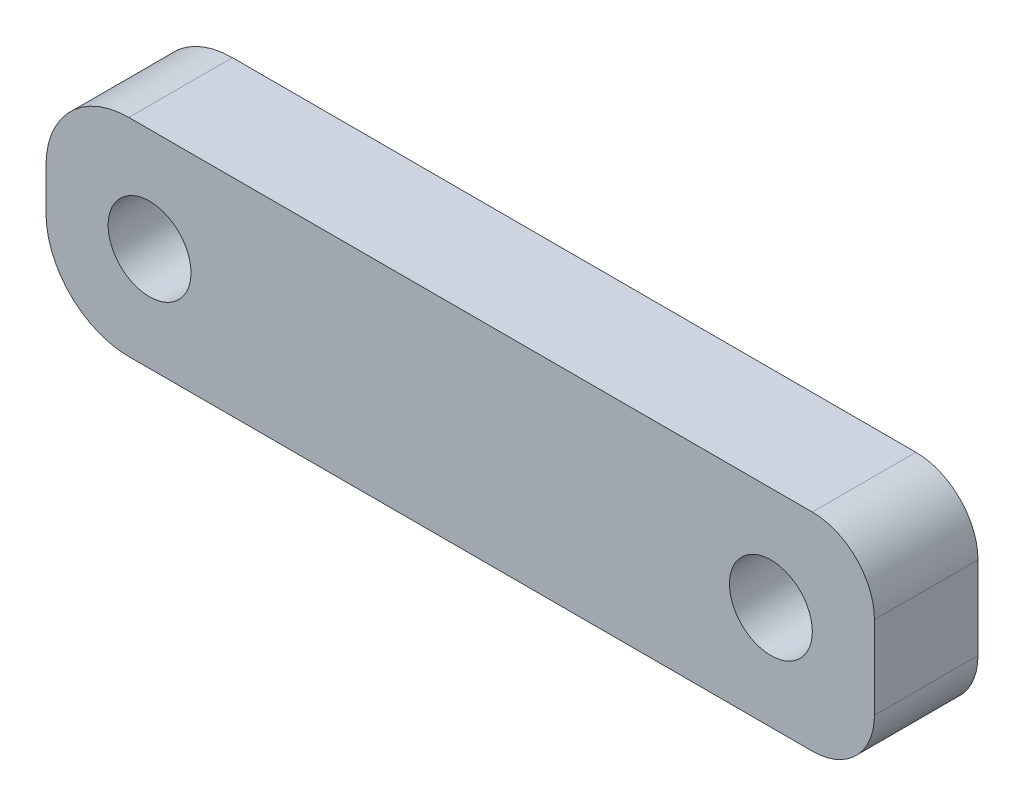
SolidWorks part; units mm, degrees
material "6061 合金"
ref_plane "前视基准面" through (0, 0, 0) normal (0, 0, 1) x (1, 0, 0)
ref_plane "上视基准面" through (0, 0, 0) normal (0, 1, 0) x (1, 0, 0)
ref_plane "右视基准面" through (0, 0, 0) normal (1, 0, 0) x (0, 0, -1)
other "Configuration Table"
sketch "草图1" plane through (0, 0, 0) normal (0, 0, 1) x (1, 0, 0)
  line L1 (4, 0) -> (37, 0)
  line L2 (0, -4) -> (0, -6)
  line L3 (4, -10) -> (37, -10)
  line L4 (40, -3) -> (40, -7)
  arc A0 (37, -10) -> (40, -7) centre (37, -7) ccw
  arc A1 (37, 0) -> (40, -3) centre (37, -3) cw
  arc A2 (0, -6) -> (4, -10) centre (4, -6) ccw
  arc A3 (4, 0) -> (0, -4) centre (4, -4) ccw
  circle A4 centre (35, -5) radius 2
  circle A5 centre (5, -5) radius 2
  point P7 (40, -10)
  point P10 (40, 0)
  point P15 (0, 0)
  dimension "D3" = 3
  dimension "D4" = 4
  dimension "D5" = 4
  dimension "D6" = 4
  dimension "D7" = 5
  dimension "D8" = 5
  dimension "D10" = 5
  dimension "D1" = 40
  dimension "D2" = 10
  dimension "D9" = 5
extrude "凸台-拉伸1" add sketch "草图1" along normal blind 5
